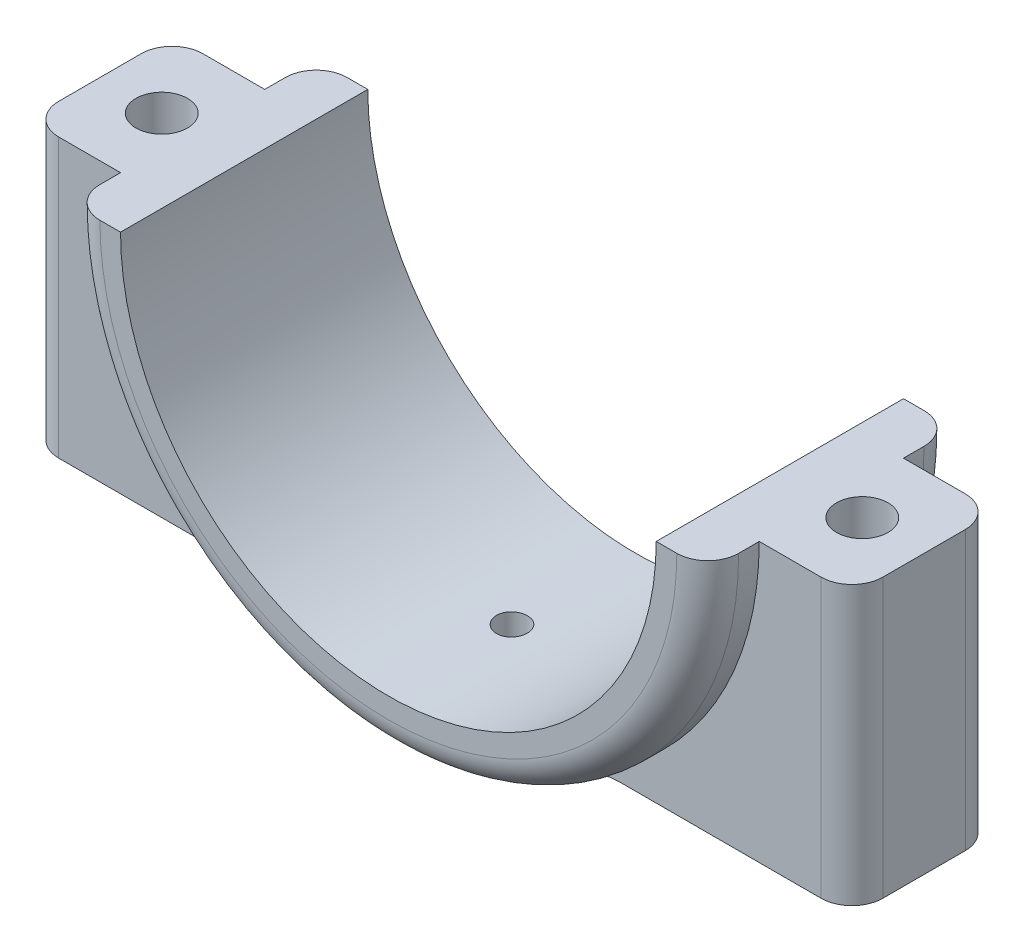
SolidWorks part; units mm, degrees
ref_plane "前视基准面" through (0, 0, 0) normal (0, 0, 1) x (1, 0, 0)
ref_plane "上视基准面" through (0, 0, 0) normal (0, 1, 0) x (1, 0, 0)
ref_plane "右视基准面" through (0, 0, 0) normal (1, 0, 0) x (0, 0, -1)
sketch "草图1" plane through (0, 0, 0) normal (0, 0, 1) x (1, 0, 0)
  line L0 (-50, 0) -> (50, 0) construction
  line L1 (0, 50) -> (0, -50) construction
  line L2 (26, 0) -> (40, 0)
  line L3 (-40, 0) -> (-26, 0)
  line L4 (-40, 0) -> (-40, -27)
  line L5 (-40, -27) -> (-15.2315, -27)
  line L6 (40, 0) -> (40, -27)
  line L7 (15.2315, -27) -> (40, -27)
  arc A0 (-26, 0) -> (26, 0) centre (0, 0) ccw
  arc A1 (-15.2315, -27) -> (15.2315, -27) centre (0, 0) ccw
  dimension "D1" = 62
  dimension "D2" = 27
  dimension "D3" = 80
  dimension "D4" = 40
extrude "拉伸1" add sketch "草图1" along normal blind 12
sketch "草图2" plane through (0, 0, 12) normal (0, 0, 1) x (1, 0, 0)
  line L0 (-40, -27) -> (-15.2315, -27) construction
  line L1 (-40, 0) -> (-40, -27) construction
  line L2 (-26, 0) -> (-40, 0) construction
  line L3 (40, 0) -> (26, 0) construction
  line L4 (40, -27) -> (40, 0) construction
  line L5 (15.2315, -27) -> (40, -27) construction
  line L6 (-40, -27) -> (-15.2315, -27)
  line L7 (-40, 0) -> (-40, -27)
  line L8 (-31, 0) -> (-40, 0)
  line L9 (40, 0) -> (31, 0)
  line L10 (40, -27) -> (40, 0)
  line L11 (15.2315, -27) -> (40, -27)
  arc A0 (-15.2315, -27) -> (15.2315, -27) centre (0, 0) ccw construction
  arc A1 (-31, 0) -> (-15.2315, -27) centre (0, 0) ccw
  arc A2 (15.2315, -27) -> (31, 0) centre (0, 0) ccw
extrude "切除-拉伸1" cut sketch "草图2" against normal blind 5
mirror "镜向1" about plane through (0, 0, 0) normal (0, 0, 1) of bodies 102
fillet "圆角1" radius 3 6 edges at (0, -31, -12) (0, -31, 12) (-40, -13.5, -7) (40, -13.5, -7) (40, -13.5, 7) (-40, -13.5, 7)
sketch "草图3" plane through (0, 0, 0) normal (0, 1, 0) x (1, 0, 0)
  line L0 (-50, 0) -> (50, 0) construction
  line L1 (-34, 14.772) -> (-34, -14.2734) construction
  circle A0 centre (-34, 0) radius 2.5
  dimension "D2" = 5
  dimension "D1" = 34
extrude "切除-拉伸2" cut sketch "草图3" against normal through all
mirror "镜向2" about plane through (0, 0, 0) normal (1, 0, 0) of "切除-拉伸2"
sketch "草图4" plane through (0, 0, 0) normal (0, 1, 0) x (1, 0, 0)
  circle A0 centre (0, 0) radius 1.5
  dimension "D1" = 3
extrude "切除-拉伸3" cut sketch "草图4" against normal through all
fillet "圆角2" radius 10 2 edges at (-15.2315, -27, 0) (15.2315, -27, 0)
